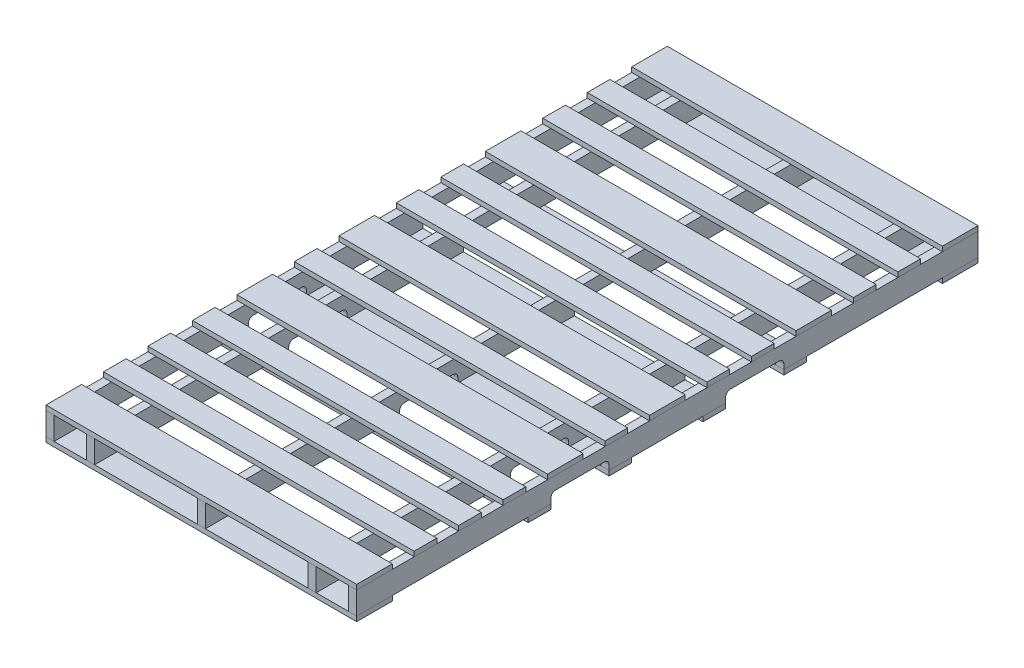
SolidWorks part; units mm, degrees
ref_plane "Front Plane" through (0, 0, 0) normal (0, 0, 1) x (1, 0, 0)
ref_plane "Top Plane" through (0, 0, 0) normal (0, 1, 0) x (1, 0, 0)
ref_plane "Right Plane" through (0, 0, 0) normal (1, 0, 0) x (0, 0, -1)
sketch "Sketch1" plane through (0, 0, 0) normal (0, 0, 1) x (1, 0, 0)
  line L0 (-609.6, 0) -> (609.6, 0) construction
  line L5 (-609.6, 63.5) -> (-609.6, -63.5) construction
  line L6 (609.6, 63.5) -> (609.6, -63.5) construction
  line L11 (-609.6, -63.5) -> (609.6, -63.5) construction
  line L12 (-609.6, 63.5) -> (609.6, 63.5) construction
  line L13 (-577.85, 63.5) -> (-577.85, -63.5) construction
  line L15 (-450.85, 63.5) -> (-450.85, -63.5) construction
  line L16 (-419.1, -63.5) -> (-419.1, 63.5) construction
  line L17 (0, 63.5) -> (0, -63.5) construction
  line L18 (-609.6, 0) -> (-577.85, 0)
  line L19 (-450.85, 0) -> (-419.1, 0)
  line L21 (577.85, 63.5) -> (577.85, -63.5) construction
  line L22 (-609.6, 44.45) -> (609.6, 44.45) construction
  line L23 (-609.6, -44.45) -> (609.6, -44.45) construction
  line L24 (419.1, 63.5) -> (450.85, 63.5)
  line L25 (419.1, 63.5) -> (419.1, -63.5)
  line L26 (419.1, -63.5) -> (450.85, -63.5)
  line L27 (450.85, 63.5) -> (450.85, -63.5)
  line L28 (-15.875, -63.5) -> (15.875, -63.5)
  line L29 (-15.875, -63.5) -> (-15.875, 63.5)
  line L30 (-15.875, 63.5) -> (15.875, 63.5)
  line L31 (15.875, -63.5) -> (15.875, 63.5)
  line L32 (-15.875, -63.5) -> (15.875, 63.5) construction
  line L33 (-15.875, 63.5) -> (15.875, -63.5) construction
  point P3 (0, 0)
  point P6 (-609.6, 0)
  point P9 (609.6, 0)
  point P23 (0, 0)
  point P32 (0, 0)
  dimension "D1" = 31.75
  dimension "Width" = 1219.2
  dimension "Height" = 127
  dimension "Maximum Fork Width" = 403.225
  dimension "D3" = 19.05
  dimension "Maximum Fork Height" = 88.9
sketch "Sketch2" plane through (0, 0, 0) normal (1, 0, 0) x (0, 0, -1)
  line L0 (1219.2, 0) -> (-1219.2, 0) construction
  point P4 (0, 0)
  dimension "Depth" = 2438.4
sketch "Sketch3" plane through (0, 0, 0) normal (0, 0, 1) x (1, 0, 0)
  line L0 (577.85, 63.5) -> (577.85, -63.5) construction
  line L5 (450.85, 63.5) -> (450.85, -63.5) construction
  line L6 (-577.85, 63.5) -> (-577.85, -63.5) construction
  line L7 (-609.6, 44.45) -> (-577.85, 44.45)
  line L8 (-609.6, 44.45) -> (-609.6, -44.45)
  line L9 (-609.6, -44.45) -> (-577.85, -44.45)
  line L10 (-577.85, 44.45) -> (-577.85, -44.45)
  line L11 (-609.6, 44.45) -> (609.6, 44.45) construction
  line L12 (450.85, 44.45) -> (419.1, 44.45)
  line L13 (-609.6, -44.45) -> (609.6, -44.45) construction
  line L14 (577.85, 44.45) -> (609.6, 44.45)
  line L15 (577.85, 44.45) -> (577.85, -44.45)
  line L16 (577.85, -44.45) -> (609.6, -44.45)
  line L17 (609.6, 44.45) -> (609.6, -44.45)
  line L18 (-609.6, 63.5) -> (-609.6, -63.5) construction
  line L19 (450.85, 44.45) -> (450.85, -44.45)
  line L20 (-450.85, 63.5) -> (-450.85, -63.5) construction
  line L21 (-450.85, 44.45) -> (-419.1, 44.45)
  line L22 (-450.85, 44.45) -> (-450.85, -44.45)
  line L23 (-450.85, -44.45) -> (-419.1, -44.45)
  line L24 (-419.1, 44.45) -> (-419.1, -44.45)
  line L25 (-419.1, -63.5) -> (-419.1, 63.5) construction
  line L26 (450.85, -44.45) -> (419.1, -44.45)
  line L27 (419.1, 44.45) -> (419.1, -44.45)
  line L28 (419.1, 63.5) -> (419.1, -63.5) construction
  line L29 (15.875, -63.5) -> (15.875, 63.5) construction
  line L30 (-15.875, -44.45) -> (15.875, -44.45)
  line L31 (-15.875, -44.45) -> (-15.875, 44.45)
  line L32 (-15.875, 44.45) -> (15.875, 44.45)
  line L33 (15.875, -44.45) -> (15.875, 44.45)
  line L34 (-15.875, -44.45) -> (15.875, 44.45) construction
  line L35 (-15.875, 44.45) -> (15.875, -44.45) construction
  point P35 (0, 0)
extrude "Boss-Extrude1" add sketch "Sketch3" along normal up to vertex (1219.2 mm away) and the other way up to vertex (1219.2 mm away) up to point (0, 0, 1219.2) other way up to point (0, 0, -1219.2)
sketch "Sketch4" plane through (0, 44.45, 0) normal (0, 1, 0) x (1, 0, 0)
  line L0 (609.6, -1219.2) -> (609.6, 1219.2) construction
  line L1 (-609.6, -1219.2) -> (609.6, -1219.2)
  line L2 (-609.6, -1219.2) -> (-609.6, -1079.5)
  line L3 (-609.6, -1079.5) -> (609.6, -1079.5)
  line L4 (609.6, -1219.2) -> (609.6, -1079.5)
  line L22 (-609.6, -1219.2) -> (-609.6, 1219.2) construction
  line L26 (-609.6, 1079.5) -> (609.6, 1079.5)
  line L27 (-609.6, 1079.5) -> (-609.6, 1219.2)
  line L28 (-609.6, 1219.2) -> (609.6, 1219.2)
  line L29 (609.6, 1079.5) -> (609.6, 1219.2)
  line L30 (0, -1079.5) -> (0, -993.775) construction
  line L31 (-609.6, -469.9) -> (609.6, -469.9)
  line L32 (-609.6, -469.9) -> (-609.6, -330.2)
  line L33 (-609.6, -330.2) -> (609.6, -330.2)
  line L34 (609.6, -469.9) -> (609.6, -330.2)
  line L35 (-609.6, -244.475) -> (609.6, -244.475)
  line L36 (-609.6, -244.475) -> (-609.6, -155.575)
  line L37 (-609.6, -155.575) -> (609.6, -155.575)
  line L38 (609.6, -244.475) -> (609.6, -155.575)
  line L39 (-609.6, 993.775) -> (609.6, 993.775)
  line L40 (-609.6, 993.775) -> (-609.6, 904.875)
  line L41 (-609.6, 904.875) -> (609.6, 904.875)
  line L42 (609.6, 993.775) -> (609.6, 904.875)
  line L43 (-609.6, 244.475) -> (609.6, 244.475)
  line L44 (-609.6, 244.475) -> (-609.6, 155.575)
  line L45 (-609.6, 155.575) -> (609.6, 155.575)
  line L46 (609.6, 244.475) -> (609.6, 155.575)
  line L47 (-609.6, 69.85) -> (609.6, 69.85)
  line L48 (-609.6, 69.85) -> (-609.6, -69.85)
  line L49 (-609.6, -69.85) -> (609.6, -69.85)
  line L50 (609.6, 69.85) -> (609.6, -69.85)
  line L51 (609.6, 819.15) -> (-609.6, 819.15)
  line L52 (609.6, 819.15) -> (609.6, 730.25)
  line L53 (609.6, 730.25) -> (-609.6, 730.25)
  line L54 (-609.6, 819.15) -> (-609.6, 730.25)
  line L55 (609.6, 644.525) -> (-609.6, 644.525)
  line L56 (609.6, 644.525) -> (609.6, 504.825)
  line L57 (609.6, 504.825) -> (-609.6, 504.825)
  line L58 (-609.6, 644.525) -> (-609.6, 504.825)
  line L59 (609.6, 419.1) -> (-609.6, 419.1)
  line L60 (609.6, 419.1) -> (609.6, 330.2)
  line L61 (609.6, 330.2) -> (-609.6, 330.2)
  line L62 (-609.6, 419.1) -> (-609.6, 330.2)
  line L63 (0, -904.875) -> (0, -819.15) construction
  line L64 (0, -730.25) -> (0, -644.525) construction
  line L65 (0, -555.625) -> (0, -469.9) construction
  line L66 (0, -330.2) -> (0, -244.475) construction
  line L67 (0, -155.575) -> (0, -69.85) construction
  line L68 (0, 69.85) -> (0, 155.575) construction
  line L69 (0, 244.475) -> (0, 330.2) construction
  line L70 (0, 419.1) -> (0, 504.825) construction
  line L71 (609.6, 993.775) -> (609.6, 1079.5) construction
  line L72 (-609.6, -555.625) -> (609.6, -555.625)
  line L73 (-609.6, -555.625) -> (-609.6, -644.525)
  line L74 (-609.6, -644.525) -> (609.6, -644.525)
  line L75 (609.6, -555.625) -> (609.6, -644.525)
  line L76 (-609.6, -819.15) -> (609.6, -819.15)
  line L77 (-609.6, -819.15) -> (-609.6, -730.25)
  line L78 (-609.6, -730.25) -> (609.6, -730.25)
  line L79 (609.6, -819.15) -> (609.6, -730.25)
  line L80 (-609.6, -904.875) -> (609.6, -904.875)
  line L81 (-609.6, -904.875) -> (-609.6, -993.775)
  line L82 (-609.6, -993.775) -> (609.6, -993.775)
  line L83 (609.6, -904.875) -> (609.6, -993.775)
  line L84 (0, 644.525) -> (0, 730.25) construction
  line L85 (0, 819.15) -> (0, 904.875) construction
  line L86 (0, 993.775) -> (0, 1079.5) construction
  dimension "D1" = 139.7
  dimension "D3" = 88.9
extrude "Boss-Extrude2" add sketch "Sketch4" along normal up to vertex (19.05 mm away) separate body up to point (-609.6, 63.5, 0)
sketch "Sketch5" plane through (0, -44.45, 0) normal (0, -1, 0) x (1, 0, 0)
  line L0 (609.6, 1219.2) -> (609.6, -1219.2) construction
  line L1 (-609.6, 1219.2) -> (609.6, 1219.2)
  line L2 (-609.6, 1219.2) -> (-609.6, 1079.5)
  line L3 (-609.6, 1079.5) -> (609.6, 1079.5)
  line L4 (609.6, 1219.2) -> (609.6, 1079.5)
  line L5 (-609.6, -1219.2) -> (609.6, -1219.2)
  line L6 (-609.6, -1219.2) -> (-609.6, -1079.5)
  line L7 (-609.6, -1079.5) -> (609.6, -1079.5)
  line L8 (609.6, -1219.2) -> (609.6, -1079.5)
  line L14 (-609.6, -228.6) -> (609.6, -228.6)
  line L15 (-609.6, 1219.2) -> (-609.6, -1219.2) construction
  line L16 (-609.6, 1219.2) -> (-609.6, 1079.5) construction
  line L17 (609.6, 1219.2) -> (609.6, 1079.5) construction
  line L18 (-609.6, 546.1) -> (609.6, 546.1)
  line L19 (-609.6, 546.1) -> (-609.6, 457.2)
  line L20 (-609.6, 457.2) -> (609.6, 457.2)
  line L21 (609.6, 546.1) -> (609.6, 457.2)
  line L22 (-609.6, -546.1) -> (609.6, -546.1)
  line L23 (-609.6, -546.1) -> (-609.6, -457.2)
  line L24 (-609.6, -457.2) -> (609.6, -457.2)
  line L25 (609.6, -546.1) -> (609.6, -457.2)
  line L26 (-609.6, -228.6) -> (-609.6, -139.7)
  line L27 (-609.6, -139.7) -> (609.6, -139.7)
  line L28 (609.6, -228.6) -> (609.6, -139.7)
  line L33 (-609.6, 139.7) -> (609.6, 139.7)
  line L34 (-609.6, 139.7) -> (-609.6, 228.6)
  line L35 (-609.6, 228.6) -> (609.6, 228.6)
  line L36 (609.6, 139.7) -> (609.6, 228.6)
  dimension "D1" = 533.4
  dimension "D2" = 533.4
  dimension "D3" = 88.9
  dimension "D4" = 139.7
  dimension "D5" = 228.6
  dimension "D6" = 279.4
extrude "Boss-Extrude3" add sketch "Sketch5" along normal up to vertex (19.05 mm away) separate body up to point (-609.6, -63.5, 0)
sketch "Sketch8" plane through (609.6, 0, 0) normal (1, 0, 0) x (0, 0, -1)
  line L1 (-228.6, -44.45) -> (-457.2, -44.45)
  line L2 (-228.6, -44.45) -> (-228.6, -25.4)
  line L3 (-247.65, -6.35) -> (-438.15, -6.35)
  line L4 (-457.2, -44.45) -> (-457.2, -25.4)
  line L5 (228.6, -44.45) -> (457.2, -44.45)
  line L6 (228.6, -44.45) -> (228.6, -25.4)
  line L7 (247.65, -6.35) -> (438.15, -6.35)
  line L8 (457.2, -44.45) -> (457.2, -25.4)
  arc A0 (438.15, -6.35) -> (457.2, -25.4) centre (438.15, -25.4) cw
  arc A1 (228.6, -25.4) -> (247.65, -6.35) centre (247.65, -25.4) cw
  arc A2 (-228.6, -25.4) -> (-247.65, -6.35) centre (-247.65, -25.4) ccw
  arc A3 (-438.15, -6.35) -> (-457.2, -25.4) centre (-438.15, -25.4) ccw
  point P18 (-457.2, -6.35)
  dimension "D3" = 19.05
  dimension "D1" = 38.1
  dimension "D2" = 228.6
extrude "Cut-Extrude2" cut sketch "Sketch8" against normal through all both and the other way through all
sketch "Sketch7" plane through (0, 0, 0) normal (0, 1, 0) x (1, 0, 0)
  line L0 (0, 1219.2) -> (609.6, 1219.2) construction
  line L2 (609.6, 1219.2) -> (609.6, 0) construction
  line L3 (609.6, 0) -> (609.6, -1219.2) construction
  line L4 (609.6, -1219.2) -> (0, -1219.2) construction
  line L5 (-609.6, -1219.2) -> (609.6, -1219.2) construction
  line L6 (-609.6, 1219.2) -> (0, 1219.2) construction
